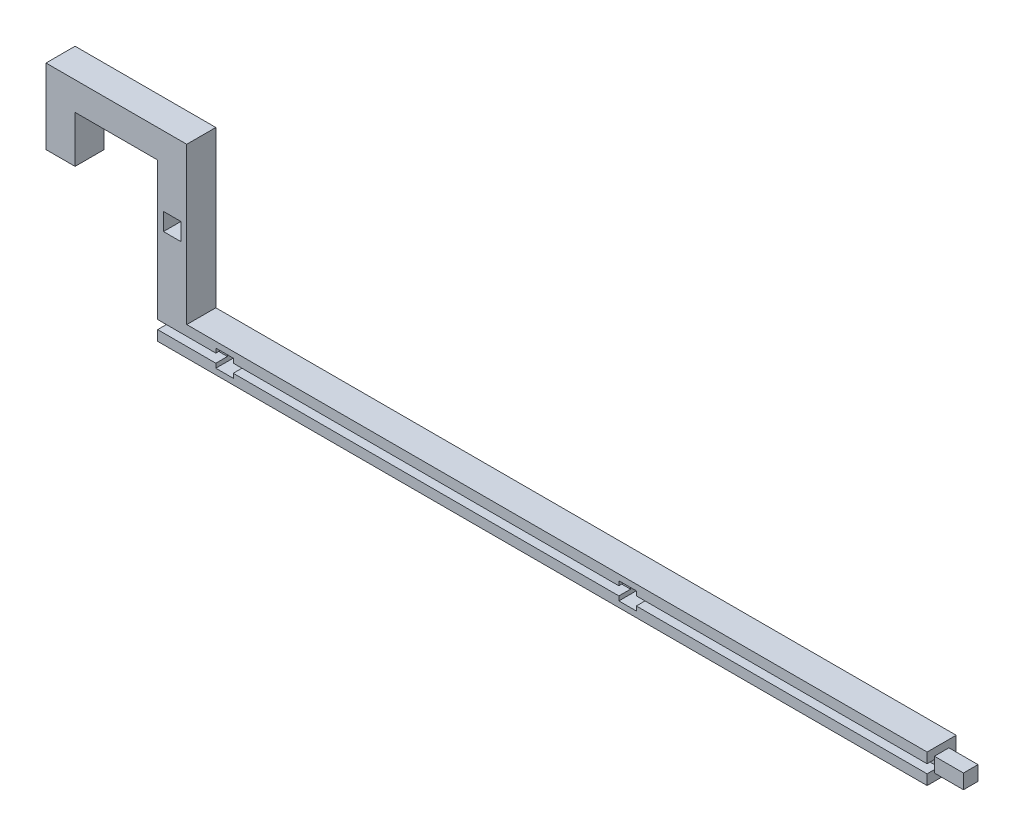
SolidWorks part; units mm, degrees
ref_plane "Front Plane" through (0, 0, 0) normal (0, 0, 1) x (1, 0, 0)
ref_plane "Top Plane" through (0, 0, 0) normal (0, 1, 0) x (1, 0, 0)
ref_plane "Right Plane" through (0, 0, 0) normal (1, 0, 0) x (0, 0, -1)
sketch "Sketch1" plane through (0, 0, 0) normal (0, 0, 1) x (1, 0, 0)
  line L0 (0, 6.7) -> (0, 8.05)
  line L5 (0, 0) -> (-5, 0)
  line L6 (-5, 0) -> (-5, 12.9)
  line L7 (-5, 12.9) -> (5.5, 12.9)
  line L8 (0, 8.05) -> (5.5, 8.05)
  line L10 (5.5, 12.9) -> (19.2, 12.9)
  line L11 (5.5, 8.05) -> (14.2, 8.05)
  line L16 (0, 6.7) -> (0, 0)
  line L17 (14.2, 8.05) -> (14.2, -18.95)
  line L18 (14.2, -18.95) -> (146.5, -18.95)
  line L19 (19.2, 12.9) -> (19.2, -13.95)
  line L20 (146.5, -18.95) -> (146.5, -13.95)
  line L21 (19.2, -13.95) -> (146.5, -13.95)
  dimension "D1" = 6.7
  dimension "D2" = 27
  dimension "D3" = 1.35
  dimension "D4" = 5
  dimension "D5" = 4.85
  dimension "D6" = 5
  dimension "D7" = 14.2
  dimension "D8" = 4.85
  dimension "D9" = 5
  dimension "D10" = 5
  dimension "D13" = 6.7
  dimension "D16" = 132.3
extrude "Boss-Extrude1" add sketch "Sketch1" along normal blind 5
sketch "Sketch2" plane through (146.5, 0, 0) normal (1, 0, 0) x (0, 0, -1)
  line L0 (-5, -18.95) -> (-5, -13.95) construction
  line L1 (-3.75, -17.7) -> (-1.25, -17.7)
  line L2 (-3.75, -17.7) -> (-3.75, -15.2)
  line L3 (-3.75, -15.2) -> (-1.25, -15.2)
  line L4 (-1.25, -17.7) -> (-1.25, -15.2)
  line L6 (-5, -13.95) -> (0, -13.95) construction
  point P4 (-3.75, -16.45)
  dimension "D1" = 2.5
  dimension "D2" = 2.5
  dimension "D3" = 1.25
  dimension "D4" = 1.25
extrude "Boss-Extrude2" add sketch "Sketch2" along normal blind 5
sketch "Sketch3" plane through (0, 0, 5) normal (0, 0, 1) x (1, 0, 0)
  line L0 (14.2, 8.05) -> (14.2, -18.95) construction
  line L1 (15.2, 0.9) -> (18.2, 0.9)
  line L2 (15.2, 0.9) -> (15.2, -2.1)
  line L3 (15.2, -2.1) -> (18.2, -2.1)
  line L4 (18.2, 0.9) -> (18.2, -2.1)
  line L5 (19.2, 12.9) -> (-5, 12.9) construction
  dimension "D1" = 3
  dimension "D2" = 3
  dimension "D3" = 1
  dimension "D4" = 12
extrude "Cut-Extrude1" cut sketch "Sketch3" against normal blind 10
sketch "Sketch4" plane through (0, 0, 5) normal (0, 0, 1) x (1, 0, 0)
  line L0 (14.2, 8.05) -> (14.2, -18.95) construction
  line L1 (14.2, -17.2) -> (146.5, -17.2)
  line L2 (14.2, -17.2) -> (14.2, -15.7)
  line L3 (14.2, -15.7) -> (146.5, -15.7)
  line L4 (146.5, -17.2) -> (146.5, -15.7)
  line L5 (146.5, -18.95) -> (146.5, -13.95) construction
  line L6 (146.5, -13.95) -> (19.2, -13.95) construction
  dimension "D1" = 1.5
  dimension "D2" = 1.75
extrude "Cut-Extrude2" cut sketch "Sketch4" against normal blind 2
sketch "Sketch5" plane through (0, 0, 0) normal (0, 0, -1) x (-1, 0, 0)
  line L0 (-146.5, -13.95) -> (-19.2, -13.95) construction
  line L1 (-27.2, -14.95) -> (-24.2, -14.95)
  line L2 (-27.2, -14.95) -> (-27.2, -17.95)
  line L3 (-27.2, -17.95) -> (-24.2, -17.95)
  line L4 (-24.2, -14.95) -> (-24.2, -17.95)
  line L5 (-96.5, -14.95) -> (-93.5, -14.95)
  line L6 (-96.5, -14.95) -> (-96.5, -17.95)
  line L7 (-96.5, -17.95) -> (-93.5, -17.95)
  line L8 (-93.5, -14.95) -> (-93.5, -17.95)
  line L9 (-14.2, 8.05) -> (-14.2, -18.95) construction
  line L10 (-146.5, -18.95) -> (-146.5, -13.95) construction
  dimension "D1" = 3
  dimension "D2" = 3
  dimension "D3" = 1
  dimension "D4" = 1
  dimension "D5" = 3
  dimension "D6" = 3
  dimension "D7" = 10
  dimension "D8" = 50
extrude "Cut-Extrude3" cut sketch "Sketch5" against normal blind 12
